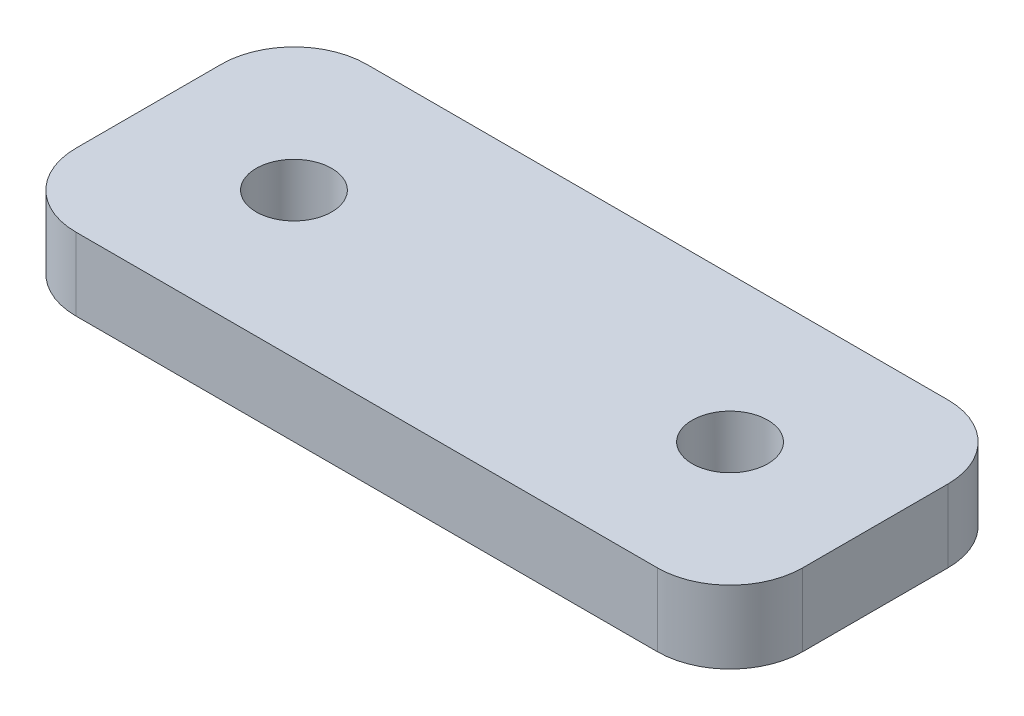
SolidWorks part; units mm, degrees
material "Acrílico (médio-alto impacto)"
ref_plane "Plano frontal" through (0, 0, 0) normal (0, 0, 1) x (1, 0, 0)
ref_plane "Plano superior" through (0, 0, 0) normal (0, 1, 0) x (1, 0, 0)
ref_plane "Plano direito" through (0, 0, 0) normal (1, 0, 0) x (0, 0, -1)
sketch "Esboço1" plane through (0, 0, 0) normal (0, 1, 0) x (1, 0, 0)
  line L1 (-25, 10) -> (25, 10)
  line L2 (-25, 10) -> (-25, -10)
  line L3 (-25, -10) -> (25, -10)
  line L4 (25, 10) -> (25, -10)
  line L5 (-25, 10) -> (25, -10) construction
  line L6 (-25, -10) -> (25, 10) construction
  point P0 (0, 0)
  dimension "D1" = 50
  dimension "D2" = 20
extrude "Ressalto-extrusão1" add sketch "Esboço1" along normal mid plane 5
sketch "Esboço2" plane through (0, 2.5, 0) normal (0, 1, 0) x (1, 0, 0)
  line L0 (0, 10) -> (0, -10) construction
  line L1 (25, 10) -> (-25, 10) construction
  line L2 (-25, -10) -> (25, -10) construction
  line L3 (-25, 0) -> (25, 0) construction
  line L4 (-25, 10) -> (-25, -10) construction
  line L5 (25, -10) -> (25, 10) construction
  circle A0 centre (-15, 0) radius 2.6
  circle A1 centre (15, 0) radius 2.6
  point P14 (0, 0)
  dimension "D1" = 5.2
  dimension "D2" = 15
extrude "Corte-extrusão1" cut sketch "Esboço2" against normal blind 6
fillet "Filete1" radius 5 4 edges at (25, 0, 10) (-25, 0, 10) (25, 0, -10) (-25, 0, -10)
